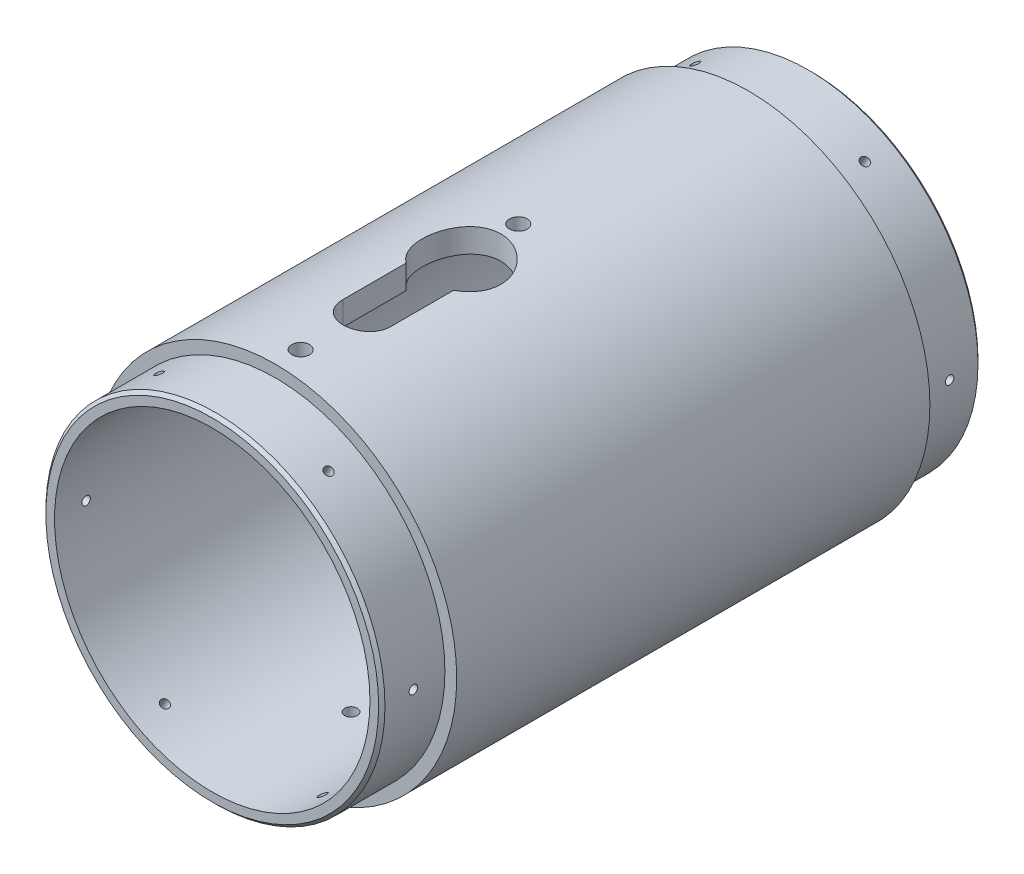
SolidWorks part; units mm, degrees
material "6061 Alloy"
ref_plane "Front Plane" through (0, 0, 0) normal (0, 0, 1) x (1, 0, 0)
ref_plane "Top Plane" through (0, 0, 0) normal (0, 1, 0) x (1, 0, 0)
ref_plane "Right Plane" through (0, 0, 0) normal (1, 0, 0) x (0, 0, -1)
sketch "Sketch1" plane through (0, 0, 0) normal (0, 0, 1) x (1, 0, 0)
  circle A0 centre (0, 0) radius 63.5
  circle A1 centre (0, 0) radius 73.025
  dimension "D1" = 146.05
  dimension "D2" = 127
extrude "Boss-Extrude1" add sketch "Sketch1" along normal mid plane 241.3
sketch "Sketch3" plane through (0, 0, 0) normal (0, 1, 0) x (1, 0, 0)
  line L0 (0, -29.845) -> (0, -58.42) construction
  line L1 (9.525, -29.845) -> (9.525, -58.42)
  line L2 (-9.525, -29.845) -> (-9.525, -58.42)
  circle A0 centre (0, -20.32) radius 15.875
  circle A1 centre (0, -20.32) radius 9.525 construction
  circle A2 centre (0, -20.32) radius 9.525 construction
  arc A3 (9.525, -29.845) -> (-9.525, -29.845) centre (0, -29.845) ccw
  arc A4 (-9.525, -58.42) -> (9.525, -58.42) centre (0, -58.42) ccw
  point P9 (0, -44.1325)
  dimension "D1" = 31.75
  dimension "D2" = 20.32
  dimension "D3" = 19.05
  dimension "D4" = 38.1
extrude "Cut-Extrude2" cut sketch "Sketch3" along normal through all contours A0 | L2 A4 L1 A3
ref_plane "Plane1" through (36.5125, 63.2415, 0) normal (0.5, 0.866, 0) x (0, 0, -1)
sketch "Sketch7" plane through (0, 0, 120.65) normal (0, 0, 1) x (1, 0, 0)
  circle A0 centre (0, 0) radius 68.2625
  circle A1 centre (0, 0) radius 73.025
  dimension "D1" = 136.525
  dimension "D2" = 146.05
extrude "Cut-Extrude3" cut sketch "Sketch7" against normal blind 25.4
hole_wizard "#8-32 Tapped Hole1" positions "Sketch9" profile "Sketch8" tap size "#8-32" standard "ANSI Inch"
sketch "Sketch9" plane through (36.5125, 63.2415, 0) normal (0.5, 0.866, 0) x (0, 0, -1)
  line L1 (-120.65, 68.2625) -> (-120.65, -68.2625) construction
  point P0 (-107.95, 0)
  dimension "D1" = 12.7
sketch "Sketch8" plane through (36.5125, 63.2415, 107.95) normal (0, 0, 1) x (-0.866, 0.5, 0)
  line L0 (0, 0) -> (0, 136.526)
  line L1 (0, 136.526) -> (1.7272, 136.526)
  line L2 (1.7272, 136.526) -> (1.7272, 0)
  line L5 (1.7272, 0) -> (0, 0)
  line L11 (0, -6.35) -> (0, 107.95) construction
  dimension "Thru Tap Drill Dia." = 3.4544
  dimension "Thru Tap Drill Depth" = 136.526
cosmetic thread "Hole Thread1" parameters "D1"=9.5485, "D2"=4.1656
pattern_circular "CirPattern1" count 6 over 360 about axis through (0, 0, 120.65) along (0, 0, 1) of "#8-32 Tapped Hole1"
mirror "Mirror1" about plane through (0, 0, 0) normal (0, 0, 1) of "CirPattern1", "#8-32 Tapped Hole1", "Cut-Extrude3"
chamfer "Chamfer1" distance 1.27 angle 45 2 edges at (68.2625, 0, -120.65) (68.2625, 0, 120.65)
ref_plane "Plane2" through (0, -73.025, 0) normal (0, -1, 0) x (0, 0, -1)
hole_wizard "CSK for #10 Flat Head Socket Cap Screw1" positions "Sketch11" profile "Sketch12" countersink size "#10" standard "ANSI Inch"
sketch "Sketch11" plane through (0, -73.025, 0) normal (0, -1, 0) x (0, 0, -1)
  circle A3 centre (-20.32, 0) radius 11.1166 construction
  arc A7 (-33.02, -9.525) -> (-33.02, 9.525) centre (-20.32, 0) ccw construction
  arc A8 (-33.02, -9.525) -> (-33.02, 9.525) centre (-20.32, 0) ccw
  point P0 (-64.77, 0)
  point P2 (24.13, 0)
  dimension "D2" = 44.45
  dimension "D3" = 88.9
sketch "Sketch12" plane through (0, -73.025, 64.77) normal (1, 0, 0) x (0, 0, -1)
  line L0 (0, 0) -> (0, 26.9338)
  line L1 (0, 26.9338) -> (2.5527, 25.4)
  line L2 (2.5527, 25.4) -> (2.5527, 3.322)
  line L3 (2.5527, 3.322) -> (5.4405, 0)
  line L5 (5.4405, 0) -> (0, 0)
  line L6 (-2.5527, 3.322) -> (-5.4405, 0) construction
  line L10 (0, 26.9338) -> (-2.5527, 25.4) construction
  line L11 (0, -6.35) -> (0, 107.95) construction
  dimension "Hole Dia." = 5.1054
  dimension "Hole Depth" = 25.4
  dimension "Near C'Sink Dia." = 10.881
  dimension "Near C'Sink Angle" = 82
  dimension "Drill Angle" = 118
ref_plane "Plane3" through (73.025, 0, 0) normal (1, 0, 0) x (0, 0, -1)
hole_wizard "9/32 (0.28125) Diameter Hole1" positions "Sketch15" profile "Sketch16" hole size "9/32" standard "ANSI Inch"
sketch "Sketch15" plane through (0, 0, 0) normal (0, 1, 0) x (1, 0, 0)
  arc A0 (9.525, -33.02) -> (-9.525, -33.02) centre (0, -20.32) ccw construction
  arc A1 (9.525, -33.02) -> (-9.525, -33.02) centre (0, -20.32) ccw
  point P0 (0, 2.54)
  point P2 (0, -85.09)
  dimension "D1" = 22.86
  dimension "D2" = 64.77
sketch "Sketch16" plane through (0, 0, -2.54) normal (1, 0, 0) x (0, 0, -1)
  line L0 (0, 0) -> (0, 73.025)
  line L1 (0, 73.025) -> (3.5719, 73.025)
  line L2 (3.5719, 73.025) -> (3.5719, 0)
  line L5 (3.5719, 0) -> (0, 0)
  line L11 (0, -6.35) -> (0, 107.95) construction
  dimension "Thru Hole Dia." = 7.1437
  dimension "Thru Hole Depth" = 73.025
equation "\"D2@Sketch11\"=\"D3@Sketch11\"/2"
